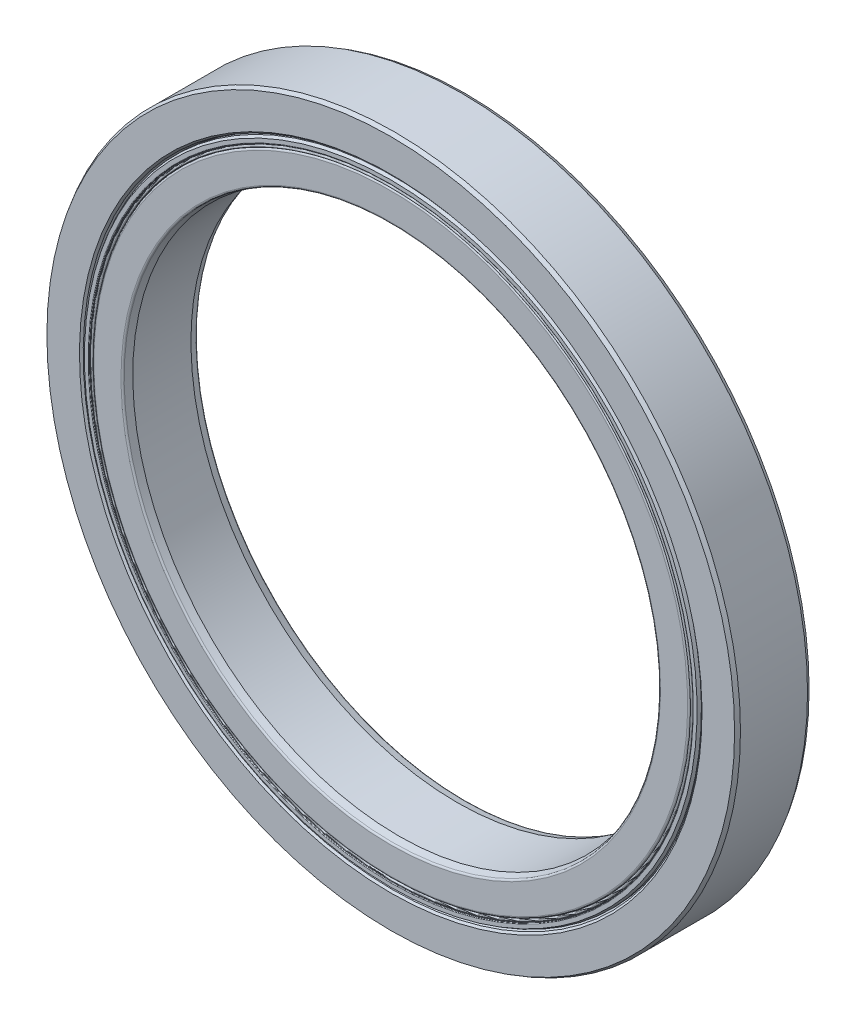
SolidWorks part; units mm, degrees
material "1060 Alloy"
ref_plane "Front Plane" through (0, 0, 0) normal (0, 0, 1) x (1, 0, 0)
ref_plane "Top Plane" through (0, 0, 0) normal (0, 1, 0) x (1, 0, 0)
ref_plane "Right Plane" through (0, 0, 0) normal (1, 0, 0) x (0, 0, -1)
sketch "Sketch1" plane through (0, 0, 0) normal (0, 0, 1) x (1, 0, 0)
  line L0 (-32.5, 0) -> (32.5, 0) construction
  line L1 (-25, 0) -> (25, 0) construction
  circle A0 centre (0, 0) radius 25 construction
  circle A1 centre (0, 0) radius 32.5 construction
  point P3 (0, 0)
  point P6 (0, 0)
  point P7 (0, -25)
  point P11 (0, -32.5)
  point P12 (0, 25)
  point P13 (0, 32.5)
  dimension "OD" = 65
  dimension "ID" = 50
sketch "Sketch2" plane through (0, 0, 0) normal (1, 0, 0) x (0, 0, -1)
  line L0 (-3.5, 32.5) -> (3.5, 32.5) construction
  line L1 (0, 32.5) -> (0, -32.5) construction
  line L2 (3.15, 32.5) -> (-3.15, 32.5)
  line L3 (-3.15, 32.5) -> (-3.5, 32.2979)
  line L4 (-3.5, 32.2979) -> (-3.5, 29.2382)
  line L5 (-2.9452, 28.925) -> (-2.7796, 28.925)
  line L6 (2.9452, 28.925) -> (2.7796, 28.925)
  line L7 (3.5, 32.2979) -> (3.5, 29.2382)
  line L8 (3.15, 32.5) -> (3.5, 32.2979)
  line L9 (-2.7796, 28.925) -> (-2.7796, 30.1167) construction
  line L10 (-2.7796, 30.1167) -> (-2.7796, 31.3083) construction
  line L11 (0, 32.5) -> (0, -32.5) construction
  line L12 (-3.5, 0) -> (3.5, 0) construction
  line L13 (3.5, 25) -> (-3.5, 25) construction
  line L14 (-3.5, 25) -> (-3.5, -25) construction
  line L15 (-3.5, -25) -> (3.5, -25) construction
  line L16 (3.5, 32.5) -> (3.5, -32.5) construction
  line L17 (-2.7796, 31.3083) -> (-2.7796, 32.5) construction
  line L18 (-2.7796, 31.3083) -> (0, 31.3083) construction
  line L20 (-2.9452, 28.925) -> (-3.325, 29.0632)
  line L21 (-3.325, 29.0632) -> (-3.5, 29.2382)
  line L26 (3.325, 29.0632) -> (3.5, 29.2382)
  line L27 (2.9452, 28.925) -> (3.325, 29.0632)
  arc A0 (-2.7796, 28.925) -> (2.7796, 28.925) centre (0, 28.4958) cw
  circle A1 centre (0, 28.4958) radius 2.8125 construction
  point P17 (0, 0)
  point P21 (0, 32.5)
  point P30 (0, -25)
  dimension "Approx. Ball Dia." = 5.625
  dimension "Width" = 7
  dimension "For Shaft Diameter" = 50
  dimension "For Housing ID" = 65
  dimension "D4" = 57.85
  dimension "D2" = 20
  dimension "D5" = 45
  dimension "D1" = 30
  dimension "D6" = 0.35
  dimension "D7" = 0.175
sketch "Sketch3" plane through (0, 0, 0) normal (1, 0, 0) x (0, 0, -1)
  line L14 (-2.9452, 28.925) -> (-3.325, 29.0632) construction
  line L15 (-3.325, 29.0632) -> (-3.5, 29.2382) construction
  line L16 (-3.5, 32.2979) -> (-3.5, 29.2382) construction
  line L17 (-3.15, 32.5) -> (-3.5, 32.2979) construction
  line L18 (3.15, 32.5) -> (-3.15, 32.5) construction
  line L19 (3.15, 32.5) -> (3.5, 32.2979) construction
  line L20 (3.5, 32.2979) -> (3.5, 29.2382) construction
  line L21 (3.325, 29.0632) -> (3.5, 29.2382) construction
  line L22 (2.9452, 28.925) -> (3.325, 29.0632) construction
  line L23 (2.9452, 28.925) -> (2.7796, 28.925) construction
  line L24 (-2.9452, 28.925) -> (-2.7796, 28.925) construction
  line L25 (-2.9452, 28.925) -> (-3.325, 29.0632)
  line L26 (-3.325, 29.0632) -> (-3.5, 29.2382)
  line L27 (-3.5, 32.2979) -> (-3.5, 29.2382)
  line L28 (-3.15, 32.5) -> (-3.5, 32.2979)
  line L29 (3.15, 32.5) -> (-3.15, 32.5)
  line L30 (3.15, 32.5) -> (3.5, 32.2979)
  line L31 (3.5, 32.2979) -> (3.5, 29.2382)
  line L32 (3.325, 29.0632) -> (3.5, 29.2382)
  line L33 (2.9452, 28.925) -> (3.325, 29.0632)
  line L34 (2.9452, 28.925) -> (2.7796, 28.925)
  line L35 (-2.9452, 28.925) -> (-2.7796, 28.925)
  arc A2 (2.7796, 28.925) -> (-2.7796, 28.925) centre (0, 28.4958) ccw construction
  arc A3 (2.7796, 28.925) -> (-2.7796, 28.925) centre (0, 28.4958) ccw
revolve "Revolve1" add sketch "Sketch3" angle 360 about L12
sketch "Sketch4" plane through (0, 0, 0) normal (1, 0, 0) x (0, 0, -1)
  line L0 (0, 32.5) -> (0, -32.5) construction
  line L1 (0, 32.5) -> (0, -32.5) construction
  line L2 (-2.7314, 25) -> (-3.3689, 25.1708)
  line L3 (-3.5, 25.3417) -> (-3.5, 27.8898)
  line L4 (3.5, -32.2979) -> (3.5, 32.2979) construction
  line L5 (-3.3231, 28.0667) -> (-2.7796, 28.0667)
  line L6 (-2.7314, 25) -> (2.7314, 25)
  line L7 (3.5, 32.2979) -> (3.5, 29.2382) construction
  line L8 (2.7314, 25) -> (3.3689, 25.1708)
  line L9 (0, 31.3083) -> (0, 25) construction
  line L10 (3.5, 25.3417) -> (3.5, 27.8898)
  line L11 (3.3231, 28.0667) -> (2.7796, 28.0667)
  line L12 (2.7314, 25) -> (2.7314, 25.1708) construction
  line L13 (2.7314, 25.1708) -> (2.7314, 25.3417) construction
  line L14 (2.7314, 25.3417) -> (2.7314, 25.5125) construction
  line L15 (2.7314, 25.5125) -> (2.7314, 25.6833) construction
  circle A0 centre (0, 28.4958) radius 2.8125 construction
  arc A1 (2.7796, 28.0667) -> (-2.7796, 28.0667) centre (0, 28.4958) cw
  arc A2 (3.5, 27.8898) -> (3.3231, 28.0667) centre (3.3231, 27.8898) ccw
  arc A3 (-3.5, 27.8898) -> (-3.3231, 28.0667) centre (-3.3231, 27.8898) cw
  arc A4 (3.3689, 25.1708) -> (3.5, 25.3417) centre (3.3231, 25.3417) ccw
  arc A5 (-3.3689, 25.1708) -> (-3.5, 25.3417) centre (-3.3231, 25.3417) cw
  point P14 (3.5, 25.206)
  point P36 (0, 25.6833)
  dimension "D1" = 15
revolve "Revolve2" add sketch "Sketch4" angle 360 about L12
sketch "Sketch5" plane through (0, 0, 0) normal (1, 0, 0) x (0, 0, -1)
  line L0 (-2.8125, 28.4958) -> (2.8125, 28.4958)
  arc A2 (-2.8125, 28.4958) -> (2.8125, 28.4958) centre (0, 28.4958) cw
  arc A3 (2.7796, 28.925) -> (-2.7796, 28.925) centre (0, 28.4958) ccw construction
revolve "Revolve3" add sketch "Sketch5" angle 360 about L0
pattern_circular "CirPattern1" count 20 over 360 about axis through (0, 0, 0) along (0, 0, 1) of bodies 104
sketch "Sketch6" plane through (0, 0, 0) normal (1, 0, 0) x (0, 0, -1)
  line L1 (-3.2402, 28.925) -> (-2.8125, 28.925)
  line L2 (-3.5, 28.775) -> (-3.5, 28.4267)
  line L3 (-3.44, 28.3667) -> (-2.8125, 28.3667)
  line L4 (-2.8125, 28.925) -> (-2.8125, 28.3667)
  line L5 (-3.5, 25.3417) -> (-3.5, 27.8898) construction
  line L6 (-3.15, 32.5) -> (-3.5, 32.2979) construction
  line L7 (0, 32.5) -> (0, 25) construction
  line L8 (3.44, 28.3667) -> (2.8125, 28.3667)
  line L9 (2.8125, 28.925) -> (2.8125, 28.3667)
  line L10 (3.2402, 28.925) -> (2.8125, 28.925)
  line L11 (3.5, 28.775) -> (3.5, 28.4267)
  line L13 (-3.3231, 28.0667) -> (-2.7796, 28.0667) construction
  line L14 (-3.5, 28.775) -> (-3.2402, 28.925)
  line L15 (-2.9452, 28.925) -> (-2.7796, 28.925) construction
  line L16 (3.5, 28.775) -> (3.2402, 28.925)
  arc A0 (-3.5, 28.4267) -> (-3.44, 28.3667) centre (-3.44, 28.4267) ccw
  circle A1 centre (0, 28.4958) radius 2.8125 construction
  arc A2 (3.5, 28.4267) -> (3.44, 28.3667) centre (3.44, 28.4267) cw
  point P26 (-3.5, 28.3667)
  dimension "D3" = 0.06
  dimension "D1" = 0.3
  dimension "D2" = 0.15
revolve "Revolve4" add sketch "Sketch6" angle 360 about L12
sketch "Sketch7" plane through (0, 0, 0) normal (1, 0, 0) x (0, 0, -1)
  line L3 (-2.8125, 28.3667) -> (-3.2941, 28.3667)
  line L4 (-3.44, 28.3667) -> (-2.8125, 28.3667) construction
  line L7 (0, 25.6833) -> (0, 25) construction
  line L8 (0, 32.5) -> (0, -32.5) construction
  line L21 (-3.2941, 28.3667) -> (-3.3679, 28.3536)
  line L22 (-3.3625, 28.2917) -> (-3.3875, 28.2917)
  line L23 (-3.3875, 28.0667) -> (-2.8125, 28.0667)
  line L24 (-2.8125, 28.0667) -> (-2.8125, 28.3667)
  line L25 (-3.3231, 28.0667) -> (-2.7796, 28.0667) construction
  line L26 (-3.5, 28.4267) -> (-3.5, 28.0667) construction
  line L27 (-3.5, 28.0667) -> (-3.3875, 28.0667) construction
  line L28 (-3.2941, 28.3667) -> (-3.2941, 28.2917) construction
  line L29 (-3.2941, 28.2917) -> (-3.2941, 28.2167) construction
  line L30 (-3.2941, 28.2167) -> (-3.2941, 28.1417) construction
  line L31 (-3.2941, 28.1417) -> (-3.2941, 28.0667) construction
  circle A2 centre (0, 28.4958) radius 2.8125 construction
  arc A9 (-3.3679, 28.3536) -> (-3.3625, 28.2917) centre (-3.3625, 28.3229) ccw
  arc A10 (-3.3875, 28.2917) -> (-3.3875, 28.0667) centre (-3.3875, 28.1792) ccw
  dimension "D1" = 0.025
  dimension "D2" = 10
revolve "Revolve5" add sketch "Sketch7" angle 360 about L12
equation "\"D4@Sketch2\"=\"OD@Sketch1\"*.89"
equation "\"D1@Sketch6\"=(\"OD@Sketch1\"-\"ID@Sketch1\")*.02"
equation "\"D2@Sketch6\"=\"D1@Sketch6\"*.5"
equation "\"D3@Sketch6\"=\"D1@Sketch6\"*.2"
equation "\"D6@Sketch2\"=\"Width@Sketch2\"*.05"
equation "\"D7@Sketch2\"=\"D6@Sketch2\"*.5"
equation "\"D1@CirPattern1\" =  ( pi * \"OD@Sketch1\" )  * .5625 / \"Approx. Ball Dia.@Sketch2\""
equation "\"Approx. Ball Dia.@Sketch2\"=(\"OD@Sketch1\"-\"ID@Sketch1\")*.5*.75"
